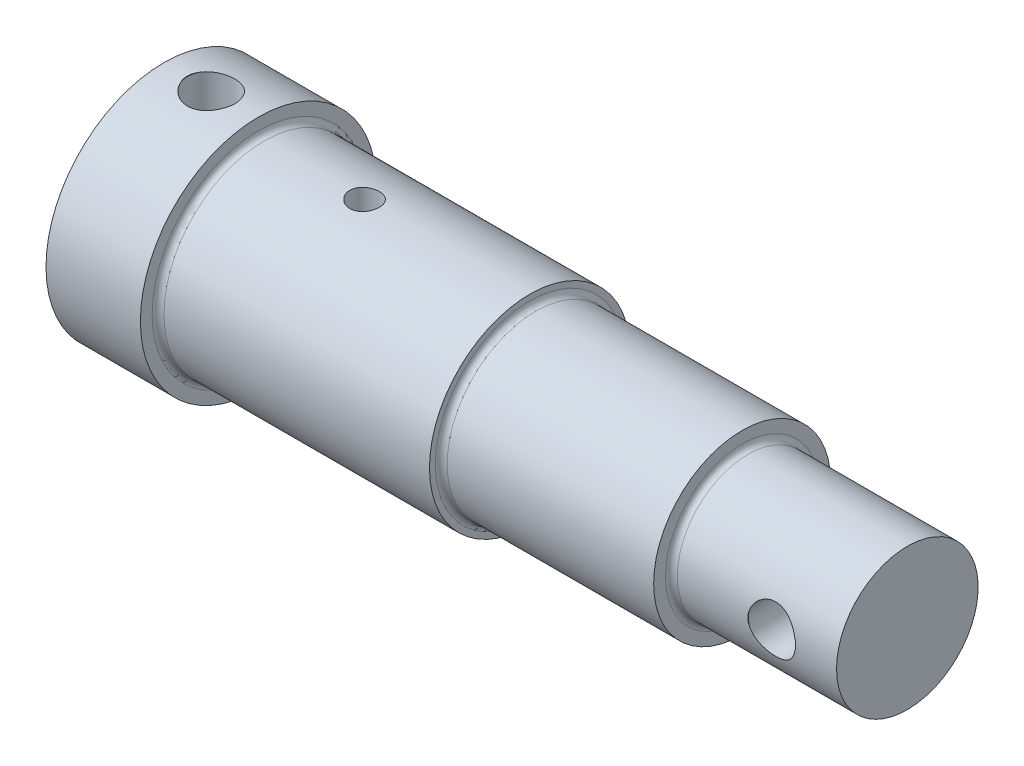
SolidWorks part; units mm, degrees
material "AISI 304"
ref_plane "Front Plane" through (0, 0, 0) normal (0, 0, 1) x (1, 0, 0)
ref_plane "Top Plane" through (0, 0, 0) normal (0, 1, 0) x (1, 0, 0)
ref_plane "Right Plane" through (0, 0, 0) normal (1, 0, 0) x (0, 0, -1)
sketch "Sketch1" plane through (0, 0, 0) normal (0, 0, 1) x (1, 0, 0)
  line L0 (0, 0) -> (64, 0)
  line L4 (50, 7.5) -> (32, 7.5)
  line L5 (32, 7.5) -> (32, 8.5)
  line L12 (1, 7.8) -> (0, 7.8)
  line L13 (0, 7.8) -> (0, 0)
  line L15 (50, 6) -> (50, 7.5)
  line L16 (1, 10) -> (1, 7.8)
  line L17 (16, 8.5) -> (32, 8.5)
  line L18 (50, 6) -> (64, 6)
  line L19 (64, 6) -> (64, 0)
  line L20 (9, 10) -> (1, 10)
  line L21 (16, 8.5) -> (9, 8.5)
  line L22 (9, 8.5) -> (9, 10)
  point P6 (15.8388, 8.5)
  dimension "D1" = 7.8
  dimension "D2" = 1
  dimension "D3" = 10
  dimension "D5" = 7.5
  dimension "D6" = 7
  dimension "D7" = 18
  dimension "D9" = 8.5
  dimension "D10" = 32
  dimension "D12" = 6
  dimension "D13" = 14
revolve "Revolve1" add sketch "Sketch1" angle 360 about L0
hole_wizard "Ø12.0mm Dowel Hole1" positions "Sketch2" profile "Sketch3" hole size "Ø12.0" standard "ANSI Metric"
sketch "Sketch2" plane through (0, 0, 0) normal (-1, 0, 0) x (0, 0, 1)
  point P0 (0, 0)
sketch "Sketch3" plane through (0, 0, 0) normal (0, 1, 0) x (0, 0, 1)
  line L0 (0, 0) -> (0, 31.6052)
  line L1 (0, 31.6052) -> (6, 28)
  line L2 (6, 28) -> (6, 0)
  line L5 (6, 0) -> (0, 0)
  line L10 (0, 31.6052) -> (-6, 28) construction
  line L11 (0, -6.35) -> (0, 107.95) construction
  dimension "Hole Dia." = 12
  dimension "Hole Depth" = 28
  dimension "Drill Angle" = 118
sketch "Sketch4" plane through (0, 0, 0) normal (0, 0, 1) x (1, 0, 0)
  line L0 (0, 0) -> (75.8878, 0) construction
  line L1 (50, -7.5) -> (50, 7.5) construction
  circle A0 centre (58.5, 0) radius 2
  dimension "D1" = 4
  dimension "D2" = 8.5
ref_plane "Plane1" through (0, -7.5, 0) normal (0, -1, 0) x (-1, 0, 0)
sketch "Sketch5" plane through (0, -7.5, 0) normal (0, -1, 0) x (-1, 0, 0)
  line L0 (-32.0658, 0) -> (-50, 0) construction
  line L1 (-50, 7.5) -> (-50, -7.5) construction
  line L2 (-32, 7.5) -> (-32, -7.5) construction
  line L3 (-48.5, 2.5) -> (-33.5, 2.5)
  line L4 (-48.5, 2.5) -> (-48.5, -2.5)
  line L5 (-48.5, -2.5) -> (-33.5, -2.5)
  line L6 (-33.5, 2.5) -> (-33.5, -2.5)
  circle A0 centre (-46, 0) radius 2.5
  circle A1 centre (-36, 0) radius 2.5
  dimension "D1" = 5
  dimension "D2" = 2.5
  dimension "D3" = 1.5
  dimension "D4" = 1.5
  dimension "D5" = 2.5
  dimension "D6" = 2.5
extrude "Cut-Extrude2" cut sketch "Sketch5" against normal blind 3 contours A0 L0 | L0 A0 | L0 A1 L3 A0 | A1 L0 A0 L5 | L0 A1 | A1 L0
sketch "Sketch6" plane through (0, 0, 0) normal (0, 1, 0) x (1, 0, 0)
  line L1 (0, 0) -> (19.9541, 0) construction
  circle A0 centre (5, 0) radius 2
  point P2 (0, 0)
  dimension "D1" = 4
ref_plane "Plane2" through (0, 8.5, 0) normal (0, 1, 0) x (1, 0, 0)
hole_wizard "M3x0.5 Tapped Hole1" positions "Sketch7" profile "Sketch9" tap size "M3x0.5" standard "ANSI Metric"
sketch "Sketch7" plane through (0, 8.5, 0) normal (0, 1, 0) x (1, 0, 0)
  line L0 (9, -10) -> (9, 10) construction
  line L1 (0, 0) -> (24.6558, 0) construction
  point P0 (18, 0)
  dimension "D1" = 9
sketch "Sketch9" plane through (18, 8.5, 0) normal (1, 0, 0) x (0, 0, 1)
  line L0 (0, 0) -> (0, 6.7511)
  line L1 (0, 6.7511) -> (1.25, 6)
  line L2 (1.25, 6) -> (1.25, 0)
  line L5 (1.25, 0) -> (0, 0)
  line L10 (0, 6.7511) -> (-1.25, 6) construction
  line L11 (0, -6.35) -> (0, 107.95) construction
  dimension "Tap Drill Dia." = 2.5
  dimension "Tap Drill Depth" = 6
  dimension "Drill Angle" = 118
cosmetic thread "Hole Thread1" parameters "D1"=2.63, "D2"=3
hole_wizard "Ø4.0mm Dowel Hole1" positions "3DSketch2" profile "Sketch11" hole size "Ø4.0" standard "ANSI Metric" end condition through all
sketch3d "3DSketch2"
  line L3 (0, 0, 0) -> (0, 18.5507, 0) construction
  line L7 (5, 0, 0) -> (5, 19.4679, 0) construction
  point P0 (5, 10, 0)
sketch "Sketch11" plane through (5, 10, 0) normal (1, 0, 0) x (0, 0, 1)
  line L0 (0, 0) -> (0, 20)
  line L1 (0, 20) -> (2.025, 20)
  line L2 (2, 19.975) -> (2, 0.025)
  line L3 (2, 0.025) -> (2.025, 0)
  line L5 (2.025, 0) -> (0, 0)
  line L6 (-2, 0.025) -> (-2.025, 0) construction
  line L7 (2.025, 20) -> (2, 19.975)
  line L8 (-2.025, 20) -> (-2, 19.975) construction
  line L11 (0, -6.35) -> (0, 107.95) construction
  dimension "Thru Hole Dia." = 4
  dimension "Thru Hole Depth" = 20
  dimension "Near C'Sink Dia." = 4.05
  dimension "Near C'Sink Angle" = 90
  dimension "Far C'Sink Dia." = 4.05
  dimension "Far C'Sink Angle" = 90
hole_wizard "Ø4.0mm Dowel Hole2" positions "3DSketch3" profile "Sketch12" hole size "Ø4.0" standard "ANSI Metric" end condition through all
sketch3d "3DSketch3"
  line L0 (58.5, 0, 0) -> (58.5, 0, -13.0835) construction
  point P0 (58.5, 0, 0)
  point P3 (58.5, 0, 0)
  point P5 (58.5, 0, 6)
sketch "Sketch12" plane through (58.5, 0, 6) normal (1, 0, 0) x (0, -1, 0)
  line L0 (0, 0) -> (0, 12)
  line L1 (0, 12) -> (2.025, 12)
  line L2 (2, 11.975) -> (2, 0.025)
  line L3 (2, 0.025) -> (2.025, 0)
  line L5 (2.025, 0) -> (0, 0)
  line L6 (-2, 0.025) -> (-2.025, 0) construction
  line L7 (2.025, 12) -> (2, 11.975)
  line L8 (-2.025, 12) -> (-2, 11.975) construction
  line L11 (0, -6.35) -> (0, 107.95) construction
  dimension "Thru Hole Dia." = 4
  dimension "Thru Hole Depth" = 12
  dimension "Near C'Sink Dia." = 4.05
  dimension "Near C'Sink Angle" = 90
  dimension "Far C'Sink Dia." = 4.05
  dimension "Far C'Sink Angle" = 90
fillet "Fillet1" radius 0.5 4 edges at (9, 0, 8.5) (32, 0, 7.5) (50, 0, 6) (1, 0, 7.8)
